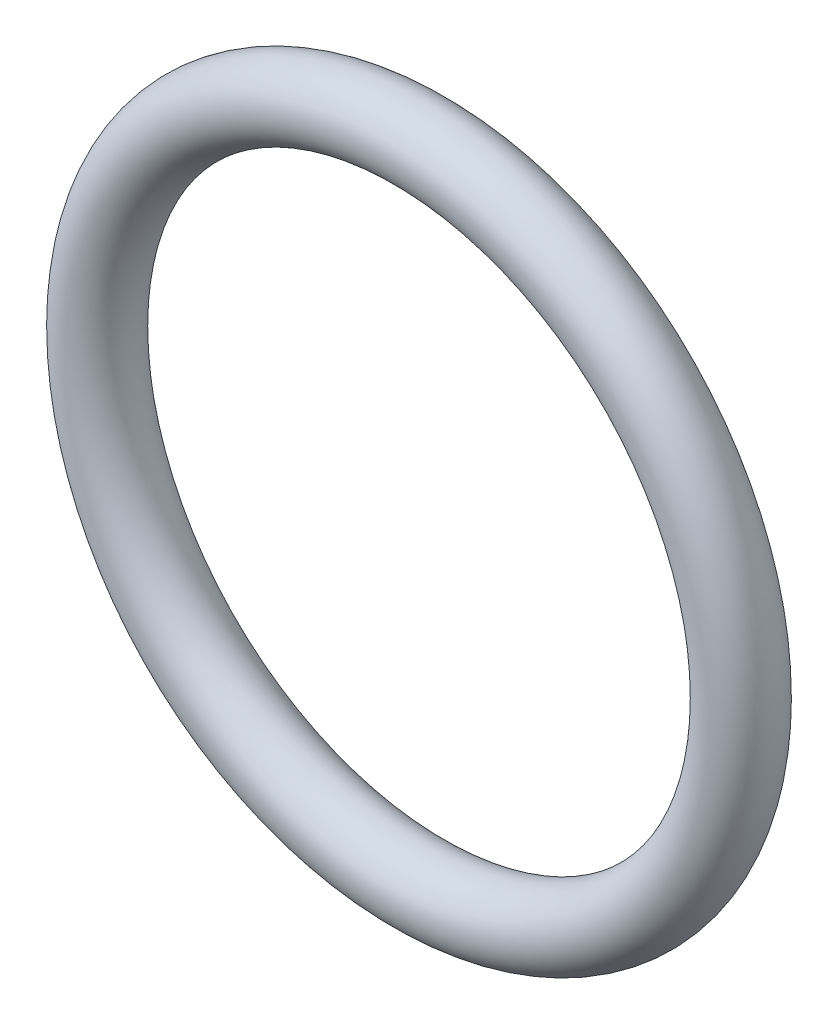
SolidWorks part; units mm, degrees
material "Rubber"
ref_plane "Front Plane" through (0, 0, 0) normal (0, 0, 1) x (1, 0, 0)
ref_plane "Top Plane" through (0, 0, 0) normal (0, 1, 0) x (1, 0, 0)
ref_plane "Right Plane" through (0, 0, 0) normal (1, 0, 0) x (0, 0, -1)
sketch "Sketch1" plane through (0, 0, 0) normal (0, 0, 1) x (1, 0, 0)
  line L0 (-7.5, 0) -> (7.5, 0) construction
  circle A0 centre (0, 0) radius 7.5
  circle A1 centre (0, 0) radius 6
  point P4 (6, 0)
  point P5 (7.5, 0)
  point P8 (0, 0)
  dimension "ID" = 12
  dimension "Width" = 1.5
  dimension "OD" = 15
sketch "Sketch2" plane through (0, 0, 0) normal (0, 1, 0) x (1, 0, 0)
  line L0 (-7.5, 0) -> (7.5, 0) construction
  line L1 (0, 0.75) -> (0, -0.75) construction
  circle A0 centre (6.75, 0) radius 0.75
  point P8 (0, 0)
  point P11 (6.75, 0.75)
revolve "Revolve1" add sketch "Sketch2" angle 360 about L1
sketch "Sketch3" plane through (0, 0, 0) normal (1, 0, 0) x (0, 0, -1)
  line L0 (-0.75, 0) -> (0.75, 0) construction
  line L1 (0.75, -6.75) -> (0.75, 6.75) construction
  point P2 (0, 0)
